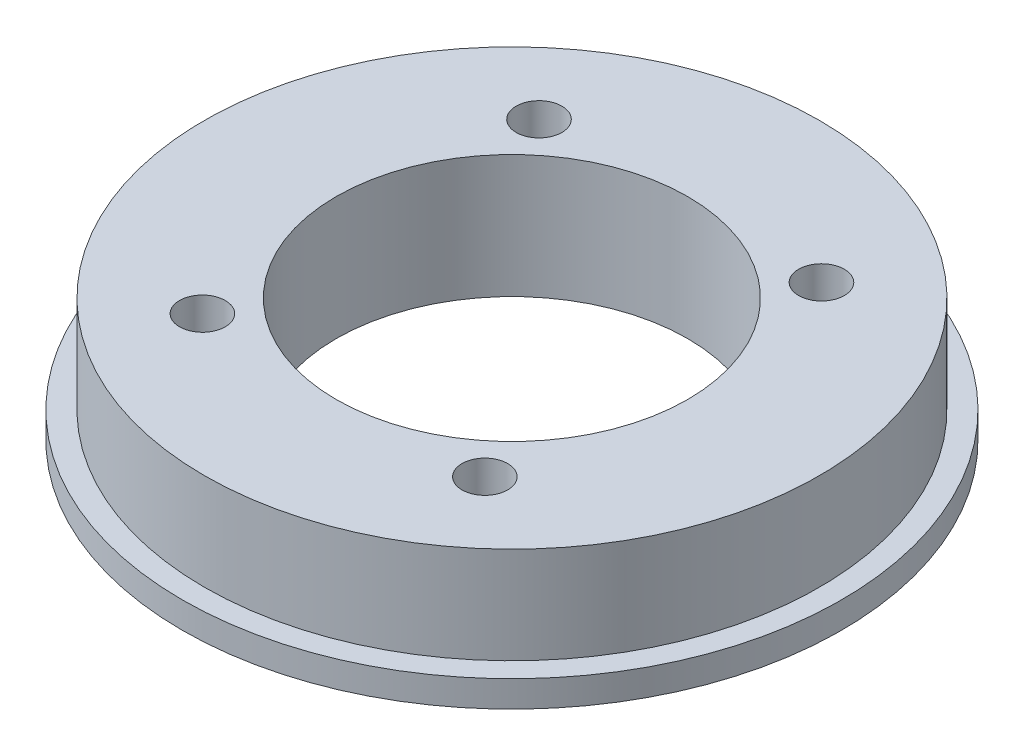
SolidWorks part; units mm, degrees
ref_plane "Front Plane" through (0, 0, 0) normal (0, 0, 1) x (1, 0, 0)
ref_plane "Top Plane" through (0, 0, 0) normal (0, 1, 0) x (1, 0, 0)
ref_plane "Right Plane" through (0, 0, 0) normal (1, 0, 0) x (0, 0, -1)
sketch "Sketch1" plane through (0, 0, 0) normal (0, 1, 0) x (1, 0, 0)
  circle A0 centre (0, 0) radius 37.5
  dimension "D1" = 75
extrude "Boss-Extrude1" add sketch "Sketch1" along normal blind 3
sketch "Sketch2" plane through (0, 3, 0) normal (0, 1, 0) x (1, 0, 0)
  circle A0 centre (0, 0) radius 35
  dimension "D1" = 70
extrude "Boss-Extrude2" add sketch "Sketch2" along normal blind 11
sketch "Sketch4" plane through (0, 14, 0) normal (0, 1, 0) x (1, 0, 0)
  line L0 (-1000, 0) -> (49000, 0) construction
  line L1 (-642.7876, -766.0444) -> (31496.5929, 37536.1777) construction
  line L2 (-642.7876, 766.0444) -> (31496.5929, -37536.1777) construction
  circle A0 centre (0, 0) radius 25 construction
  circle A1 centre (-16.0697, 19.1511) radius 2.6
  circle A2 centre (16.0697, 19.1511) radius 2.6
  circle A3 centre (16.0697, -19.1511) radius 2.6
  circle A4 centre (-16.0697, -19.1511) radius 2.6
  dimension "D1" = 50
  dimension "D2" = 5.2
  dimension "D3" = 5.2
  dimension "D4" = 5.2
  dimension "D5" = 5.2
  dimension "D6" = 50
  dimension "D7" = 80
extrude "Cut-Extrude2" cut sketch "Sketch4" against normal through all
sketch "Sketch5" plane through (0, 14, 0) normal (0, 1, 0) x (1, 0, 0)
  circle A0 centre (0, 0) radius 20
  dimension "D1" = 40
extrude "Cut-Extrude3" cut sketch "Sketch5" against normal through all
sketch "Sketch6" plane through (0, 0, 0) normal (0, -1, 0) x (1, 0, 0)
  circle A0 centre (16.0697, -19.1511) radius 4.75
  circle A1 centre (-16.0697, -19.1511) radius 4.75
  circle A2 centre (16.0697, 19.1511) radius 4.75
  circle A3 centre (-16.0697, 19.1511) radius 4.75
  dimension "D1" = 9.5
  dimension "D2" = 9.5
  dimension "D3" = 9.5
  dimension "D4" = 9.5
extrude "Cut-Extrude4" cut sketch "Sketch6" against normal blind 3
